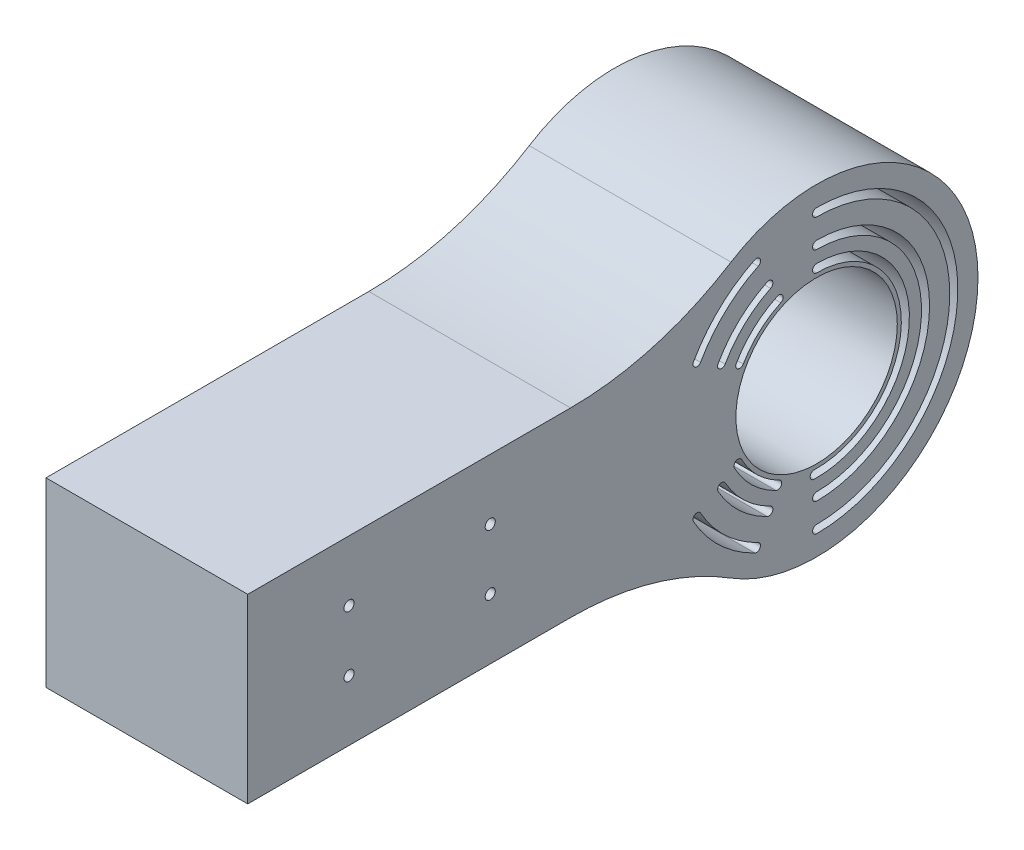
SolidWorks part; units mm, degrees
ref_plane "Plano frontal" through (0, 0, 0) normal (0, 0, 1) x (1, 0, 0)
ref_plane "Plano superior" through (0, 0, 0) normal (0, 1, 0) x (1, 0, 0)
ref_plane "Plano direito" through (0, 0, 0) normal (1, 0, 0) x (0, 0, -1)
sketch "Esboço2" plane through (0, 0, 0) normal (1, 0, 0) x (0, 0, -1)
  line L1 (-50.9816, -22.5) -> (29.0184, -22.5)
  line L2 (-50.9816, -22.5) -> (-50.9816, 22.5)
  line L3 (-50.9816, 22.5) -> (29.0184, 22.5)
  arc A0 (68.789, -33.913) -> (68.789, 33.913) centre (90, 0) ccw
  circle A1 centre (90, 0) radius 20
  arc A2 (29.0184, -22.5) -> (68.789, -33.913) centre (29.0184, -97.5) cw
  arc A3 (29.0184, 22.5) -> (68.789, 33.913) centre (29.0184, 97.5) ccw
  arc A4 (67.3394, -12.7475) -> (78.6039, -23.3694) centre (90, 0) ccw
  arc A5 (65.5963, -13.7281) -> (77.7273, -25.167) centre (90, 0) ccw
  arc A6 (61.2385, -16.1795) -> (75.5357, -29.6612) centre (90, 0) ccw
  arc A7 (59.4954, -17.1601) -> (74.6591, -31.4588) centre (90, 0) ccw
  arc A8 (59.4954, 17.1601) -> (61.2385, 16.1795) centre (60.367, 16.6698) ccw
  arc A9 (65.5963, 13.7281) -> (67.3394, 12.7475) centre (66.4679, 13.2378) ccw
  arc A10 (65.5963, -13.7281) -> (67.3394, -12.7475) centre (66.4679, -13.2378) cw
  arc A11 (61.2385, -16.1795) -> (59.4954, -17.1601) centre (60.367, -16.6698) ccw
  arc A12 (74.6591, 31.4588) -> (59.4954, 17.1601) centre (90, 0) ccw
  arc A13 (75.5357, 29.6612) -> (61.2385, 16.1795) centre (90, 0) ccw
  arc A14 (77.7273, 25.167) -> (65.5963, 13.7281) centre (90, 0) ccw
  arc A15 (78.6039, 23.3694) -> (67.3394, 12.7475) centre (90, 0) ccw
  arc A16 (90, -35) -> (90, 35) centre (90, 0) ccw
  arc A17 (90, -33) -> (90, 33) centre (90, 0) ccw
  arc A18 (90, -28) -> (90, 28) centre (90, 0) ccw
  arc A19 (90, -26) -> (90, 26) centre (90, 0) ccw
  arc A20 (78.6039, -23.3694) -> (77.7273, -25.167) centre (78.1656, -24.2682) cw
  arc A21 (75.5357, -29.6612) -> (74.6591, -31.4588) centre (75.0974, -30.56) cw
  arc A22 (77.7273, 25.167) -> (78.6039, 23.3694) centre (78.1656, 24.2682) cw
  arc A23 (74.6591, 31.4588) -> (75.5357, 29.6612) centre (75.0974, 30.56) cw
  arc A24 (90, 35) -> (90, 33) centre (90, 34) ccw
  arc A25 (90, 28) -> (90, 26) centre (90, 27) ccw
  arc A26 (90, -26) -> (90, -28) centre (90, -27) ccw
  arc A27 (90, -33) -> (90, -35) centre (90, -34) ccw
  arc A28 (70.9522, 11.0083) -> (80.7011, 19.9382) centre (90, 0) cw construction
  arc A29 (80.2784, 20.8444) -> (70.0864, 11.5086) centre (90, 0) ccw
  arc A30 (81.1238, 19.0319) -> (71.818, 10.5079) centre (90, 0) ccw
  arc A31 (81.1238, 19.0319) -> (80.2784, 20.8444) centre (80.7011, 19.9382) ccw
  arc A32 (70.0864, 11.5086) -> (71.818, 10.5079) centre (70.9522, 11.0083) ccw
  arc A33 (80.3572, -19.7741) -> (70.527, -10.2373) centre (90, 0) cw construction
  arc A34 (69.6419, -10.7026) -> (79.9188, -20.6729) centre (90, 0) ccw
  arc A35 (71.4121, -9.772) -> (80.7955, -18.8753) centre (90, 0) ccw
  arc A36 (71.4121, -9.772) -> (69.6419, -10.7026) centre (70.527, -10.2373) ccw
  arc A37 (79.9188, -20.6729) -> (80.7955, -18.8753) centre (80.3572, -19.7741) ccw
  arc A38 (89.4054, -21.992) -> (90, 22) centre (90, 0) ccw construction
  arc A39 (89.3784, -22.9916) -> (90, 23) centre (90, 0) ccw
  arc A40 (89.4324, -20.9923) -> (90, 21) centre (90, 0) ccw
  arc A41 (89.4324, -20.9923) -> (89.3784, -22.9916) centre (89.4054, -21.992) ccw
  arc A42 (90, 23) -> (90, 21) centre (90, 22) ccw
  point P0 (0, 0)
  point P1 (-50.9816, 0)
  point P51 (75.14, 16.2228)
  point P59 (74.681, -15.7902)
  point P64 (111.998, -0.2973)
  dimension "D1" = 80
  dimension "D3" = 40
  dimension "D4" = 75
  dimension "D7" = 5
  dimension "D8" = 5
  dimension "D9" = 2
  dimension "D10" = 2
  dimension "D11" = 2
  dimension "D12" = 3
  dimension "D13" = 2
  dimension "D14" = 3
  dimension "D15" = 2
  dimension "D16" = 3
  dimension "D2" = 45
  dimension "D5" = 80
  dimension "D6" = 90
extrude "Ressalto-extrusão1" add sketch "Esboço2" along normal mid plane 50
sketch "Esboço3" plane through (-25, 0, 0) normal (-1, 0, 0) x (0, 0, 1)
  line L1 (-29.0184, 22.5) -> (50.9816, 22.5) construction
  line L2 (50.9816, -22.5) -> (-29.0184, -22.5) construction
  circle A0 centre (25.8816, 7.5) radius 1.25
  circle A1 centre (-9.1184, 7.5) radius 1.25
  circle A2 centre (-9.1184, -7.5) radius 1.25
  circle A3 centre (25.8816, -7.5) radius 1.25
  dimension "D1" = 35
  dimension "D2" = 15
  dimension "D3" = 15
  dimension "D4" = 2.5
  dimension "D5" = 15
  dimension "D6" = 2.5
  dimension "D7" = 2.5
extrude "Corte-extrusão1" cut sketch "Esboço3" against normal through all
